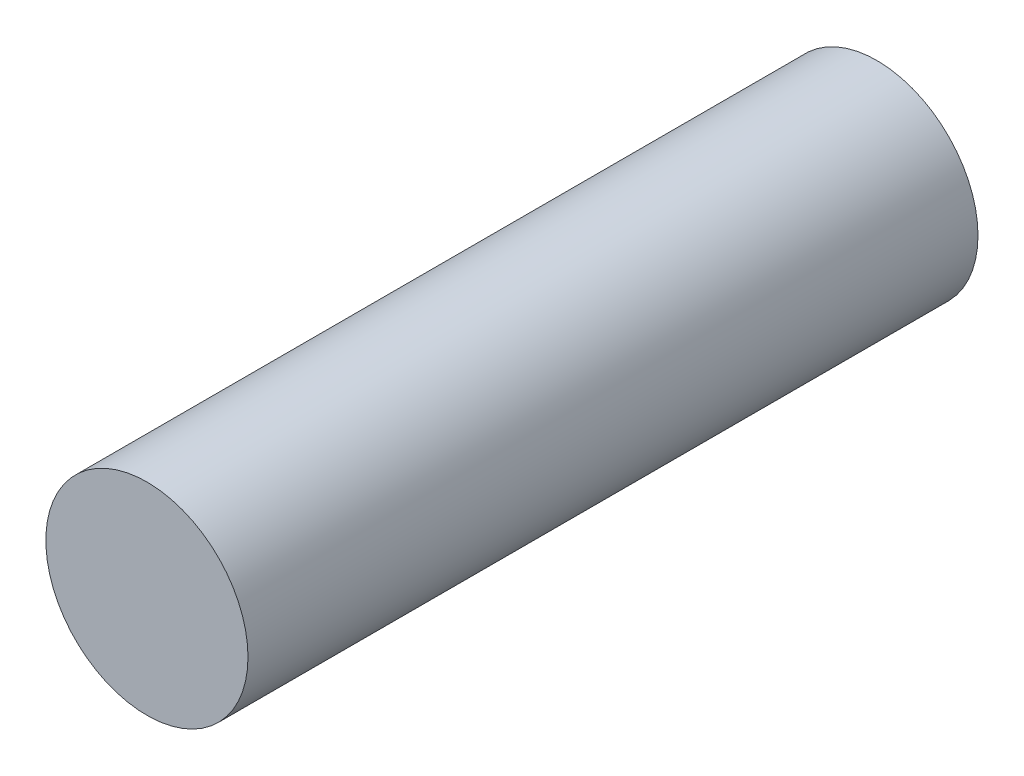
SolidWorks part; units mm, degrees
ref_plane "Plan de face" through (0, 0, 0) normal (0, 0, 1) x (1, 0, 0)
ref_plane "Plan de dessus" through (0, 0, 0) normal (0, 1, 0) x (1, 0, 0)
ref_plane "Plan de droite" through (0, 0, 0) normal (1, 0, 0) x (0, 0, -1)
sketch "Esquisse1" plane through (0, 0, 0) normal (0, 0, 1) x (1, 0, 0)
  circle A0 centre (0, 0) radius 9
  dimension "D1" = 18
extrude "Boss.-Extru.1" add sketch "Esquisse1" along normal blind 65 contours A0
